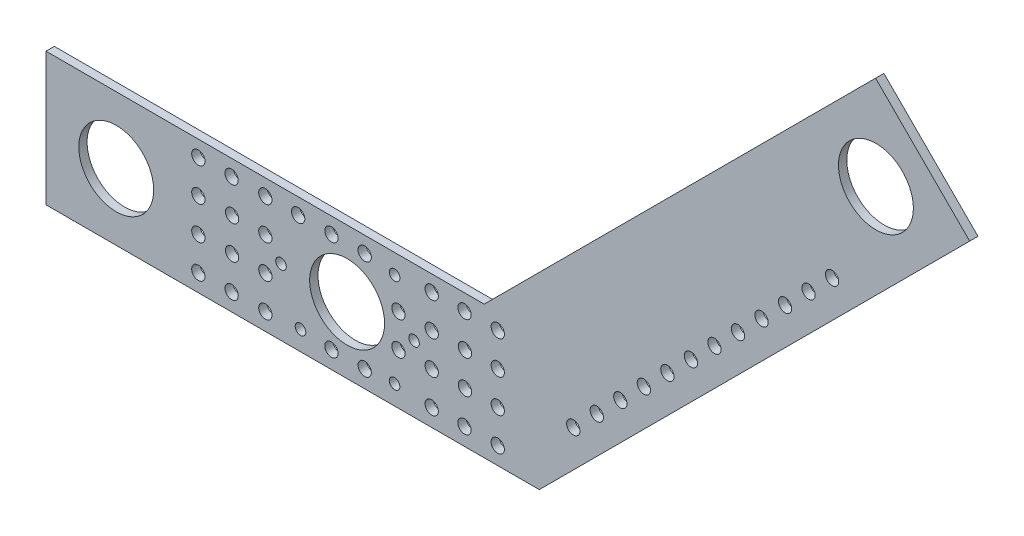
SolidWorks part; units mm, degrees
ref_plane "Front Plane" through (0, 0, 0) normal (0, 0, 1) x (1, 0, 0)
ref_plane "Top Plane" through (0, 0, 0) normal (0, 1, 0) x (1, 0, 0)
ref_plane "Right Plane" through (0, 0, 0) normal (1, 0, 0) x (0, 0, -1)
sketch "Sketch1" plane through (0, 0, 0) normal (0, 0, 1) x (1, 0, 0)
  line L0 (-59.6938, 4.2713) -> (-59.6938, -46.5287)
  line L1 (-59.6938, -46.5287) -> (128.6141, -46.5287)
  line L2 (128.6141, -46.5287) -> (292.9114, 117.7686)
  line L3 (292.9114, 117.7686) -> (256.9904, 153.6896)
  line L4 (256.9904, 153.6896) -> (107.5721, 4.2713)
  line L5 (107.5721, 4.2713) -> (-59.6938, 4.2713)
  circle A0 centre (24.0402, -14.5121) radius 2.54 construction
  circle A1 centre (74.8402, -14.5121) radius 2.54 construction
  circle A2 centre (87.5402, -14.5121) radius 2.54 construction
  circle A3 centre (100.2402, -14.5121) radius 2.54 construction
  circle A4 centre (100.2402, -27.2121) radius 2.54 construction
  circle A5 centre (87.5402, -27.2121) radius 2.54 construction
  circle A6 centre (74.8402, -27.2121) radius 2.54 construction
  circle A7 centre (24.0402, -27.2121) radius 2.54 construction
  circle A8 centre (11.3402, -27.2121) radius 2.54 construction
  circle A9 centre (11.3402, -14.5121) radius 2.54 construction
  circle A10 centre (11.1589, -1.8121) radius 2.54 construction
  circle A11 centre (24.0402, -1.8121) radius 2.54 construction
  circle A12 centre (36.5589, -1.8121) radius 2.54 construction
  circle A13 centre (49.2589, -1.8121) radius 2.54 construction
  circle A14 centre (61.9589, -1.8121) radius 2.54 construction
  circle A15 centre (87.5402, -1.8121) radius 2.54 construction
  circle A16 centre (100.0589, -1.8121) radius 2.54 construction
  circle A17 centre (112.7589, -1.8121) radius 2.54 construction
  circle A18 centre (112.7589, -14.5121) radius 2.54 construction
  circle A19 centre (112.7589, -27.2121) radius 2.54 construction
  circle A20 centre (112.7589, -39.9121) radius 2.54 construction
  circle A21 centre (100.0589, -39.9121) radius 2.54 construction
  circle A22 centre (87.5402, -39.9121) radius 2.54 construction
  circle A23 centre (61.9589, -39.9121) radius 2.54 construction
  circle A24 centre (49.2589, -39.9121) radius 2.54 construction
  circle A25 centre (24.0402, -39.9121) radius 2.54 construction
  circle A26 centre (11.1589, -39.9121) radius 2.54 construction
  circle A27 centre (-1.5411, -39.9121) radius 2.54 construction
  circle A28 centre (-1.5411, -27.2121) radius 2.54 construction
  circle A29 centre (-1.5411, -14.5121) radius 2.54 construction
  circle A30 centre (-1.5411, -1.8121) radius 2.54 construction
  circle A31 centre (73.3783, -3.1782) radius 2.0193 construction
  circle A32 centre (80.8178, -21.1387) radius 2.0193 construction
  circle A33 centre (73.3783, -39.0992) radius 2.0193 construction
  circle A34 centre (37.4573, -39.0992) radius 2.0193 construction
  circle A35 centre (30.0178, -21.1387) radius 2.0193 construction
  circle A36 centre (55.2538, -21.1287) radius 14.3002 construction
  circle A37 centre (-32.8842, -21.1287) radius 14.3002 construction
  circle A38 centre (24.0402, -14.5121) radius 2.54
  circle A39 centre (74.8402, -14.5121) radius 2.54
  circle A40 centre (87.5402, -14.5121) radius 2.54
  circle A41 centre (100.2402, -14.5121) radius 2.54
  circle A42 centre (100.2402, -27.2121) radius 2.54
  circle A43 centre (87.5402, -27.2121) radius 2.54
  circle A44 centre (74.8402, -27.2121) radius 2.54
  circle A45 centre (24.0402, -27.2121) radius 2.54
  circle A46 centre (11.3402, -27.2121) radius 2.54
  circle A47 centre (11.3402, -14.5121) radius 2.54
  circle A48 centre (11.1589, -1.8121) radius 2.54
  circle A49 centre (24.0402, -1.8121) radius 2.54
  circle A50 centre (36.5589, -1.8121) radius 2.54
  circle A51 centre (49.2589, -1.8121) radius 2.54
  circle A52 centre (61.9589, -1.8121) radius 2.54
  circle A53 centre (87.5402, -1.8121) radius 2.54
  circle A54 centre (100.0589, -1.8121) radius 2.54
  circle A55 centre (112.7589, -1.8121) radius 2.54
  circle A56 centre (112.7589, -14.5121) radius 2.54
  circle A57 centre (112.7589, -27.2121) radius 2.54
  circle A58 centre (112.7589, -39.9121) radius 2.54
  circle A59 centre (100.0589, -39.9121) radius 2.54
  circle A60 centre (87.5402, -39.9121) radius 2.54
  circle A61 centre (61.9589, -39.9121) radius 2.54
  circle A62 centre (49.2589, -39.9121) radius 2.54
  circle A63 centre (24.0402, -39.9121) radius 2.54
  circle A64 centre (11.1589, -39.9121) radius 2.54
  circle A65 centre (-1.5411, -39.9121) radius 2.54
  circle A66 centre (-1.5411, -27.2121) radius 2.54
  circle A67 centre (-1.5411, -14.5121) radius 2.54
  circle A68 centre (-1.5411, -1.8121) radius 2.54
  circle A69 centre (73.3783, -3.1782) radius 2.0193
  circle A70 centre (80.8178, -21.1387) radius 2.0193
  circle A71 centre (73.3783, -39.0992) radius 2.0193
  circle A72 centre (37.4573, -39.0992) radius 2.0193
  circle A73 centre (30.0178, -21.1387) radius 2.0193
  circle A74 centre (55.2538, -21.1287) radius 14.3002
  circle A75 centre (-32.8842, -21.1287) radius 14.3002
  circle A76 centre (257.1207, 117.8989) radius 14.3002
  circle A77 centre (141.5888, -19.431) radius 2.54
  circle A78 centre (150.569, -10.4508) radius 2.54
  circle A79 centre (159.5493, -1.4705) radius 2.54
  circle A80 centre (168.5296, 7.5097) radius 2.54
  circle A81 centre (177.5098, 16.49) radius 2.54
  circle A82 centre (186.4901, 25.4703) radius 2.54
  circle A83 centre (195.4703, 34.4505) radius 2.54
  circle A84 centre (204.4506, 43.4308) radius 2.54
  circle A85 centre (213.4308, 52.411) radius 2.54
  circle A86 centre (222.4111, 61.3913) radius 2.54
  circle A87 centre (231.3914, 70.3715) radius 2.54
  circle A88 centre (240.3716, 79.3518) radius 2.54
  point P124 (133.2268, -31.7607)
  point P125 (141.5888, -19.431)
  dimension "D4" = 245.11
  dimension "D6" = 12
  dimension "D1" = 50.8
  dimension "D2" = 50.8
  dimension "D3" = 135
  dimension "D5" = 25.4
extrude "Boss-Extrude1" add sketch "Sketch1" along normal blind 3.175
